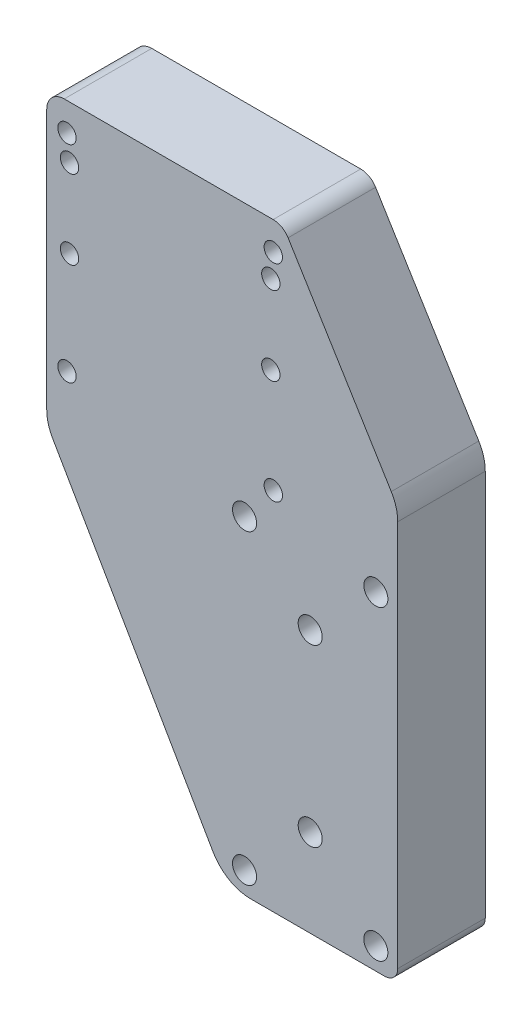
SolidWorks part; units mm, degrees
ref_plane "Front Plane" through (0, 0, 0) normal (0, 0, 1) x (1, 0, 0)
ref_plane "Top Plane" through (0, 0, 0) normal (0, 1, 0) x (1, 0, 0)
ref_plane "Right Plane" through (0, 0, 0) normal (1, 0, 0) x (0, 0, -1)
sketch "Sketch1" plane through (0, 0, 0) normal (0, 0, 1) x (1, 0, 0)
  line L0 (-130, 510) -> (13.8884, 510) construction
  line L1 (-170.2, 540.8246) -> (-129.3094, 470)
  line L2 (-116.2253, 607) -> (-90, 564.2553)
  line L15 (-90, 473) -> (-90, 564.2553)
  line L16 (-90, 473) -> (-90, 547) construction
  line L24 (-170.2, 540.8246) -> (-170.2, 607)
  line L25 (-170.2, 607) -> (-116.2253, 607)
  line L183 (-129.3094, 470) -> (-93, 470)
  arc A1 (-113.8, 602.2) -> (-116.8, 605.2) centre (-116.8, 602.2) ccw construction
  arc A13 (-90, 473) -> (-93, 470) centre (-93, 473) cw
extrude "Boss-Extrude1" add sketch "Sketch1" along normal blind 20
fillet "Fillet1" radius 10 3 edges at (-129.3094, 470, 10) (-170.2, 540.8246, 10) (-90, 564.2553, 10)
sketch "Sketch2" plane through (0, 0, 20) normal (0, 0, 1) x (1, 0, 0)
  circle A0 centre (-142, 577) radius 20
  dimension "D1" = 40
hole_wizard "Tap Drill for M5 Tap1" positions "Sketch5" profile "Sketch6" hole size "M5" standard "ISO" end condition through all
sketch "Sketch5" plane through (0, 0, 0) normal (0, 0, -1) x (-1, 0, 0)
  line L1 (119, 595) -> (119, 577)
  line L2 (119, 595) -> (165, 595)
  line L3 (165, 595) -> (165, 577)
  line L4 (119, 577) -> (165, 577)
  circle A1 centre (119, 595) radius 2.1
  point P2 (119, 595)
  point P4 (119, 577)
  point P6 (165, 577)
  point P8 (165, 595)
  dimension "D1" = 18
  dimension "D2" = 46
  dimension "D3" = 46
  dimension "D4" = 18
sketch "Sketch6" plane through (-119, 595, 0) normal (1, 0, 0) x (0, 1, 0)
  line L0 (0, 0) -> (0, 20)
  line L1 (0, 20) -> (2.1, 20)
  line L2 (2.1, 20) -> (2.1, 0)
  line L5 (2.1, 0) -> (0, 0)
  line L11 (0, -6.35) -> (0, 107.95) construction
  dimension "Thru Hole Dia." = 4.2
  dimension "Thru Hole Depth" = 20
hole_wizard "M5 Clearance Hole1" positions "Sketch7" profile "Sketch8" hole size "M5" standard "ISO" end condition through all
sketch "Sketch7" plane through (0, 0, 20) normal (0, 0, 1) x (1, 0, 0)
  point P0 (-95, 545)
  point P2 (-125, 545)
  point P4 (-125, 475)
  point P6 (-95, 475)
  point P8 (-110, 490)
  point P10 (-110, 530)
sketch "Sketch8" plane through (-95, 545, 20) normal (1, 0, 0) x (0, -1, 0)
  line L0 (0, 0) -> (0, 20)
  line L1 (0, 20) -> (2.75, 20)
  line L2 (2.75, 20) -> (2.75, 0)
  line L5 (2.75, 0) -> (0, 0)
  line L11 (0, -6.35) -> (0, 107.95) construction
  dimension "Thru Hole Dia." = 5.5
  dimension "Thru Hole Depth" = 20
hole_wizard "Tap Drill for M5 Tap2" positions "Sketch9" profile "Sketch10" hole size "M5" standard "ISO" end condition through all
sketch "Sketch9" plane through (0, 0, 20) normal (0, 0, 1) x (1, 0, 0)
  point P0 (-165.57, 553.43)
  point P2 (-165.57, 600.57)
  point P4 (-118.43, 553.43)
  point P6 (-118.43, 600.57)
sketch "Sketch10" plane through (-165.57, 553.43, 20) normal (1, 0, 0) x (0, -1, 0)
  line L0 (0, 0) -> (0, 20)
  line L1 (0, 20) -> (2.1, 20)
  line L2 (2.1, 20) -> (2.1, 0)
  line L5 (2.1, 0) -> (0, 0)
  line L11 (0, -6.35) -> (0, 107.95) construction
  dimension "Thru Hole Dia." = 4.2
  dimension "Thru Hole Depth" = 20
fillet "Fillet2" radius 4 2 edges at (-116.2253, 607, 10) (-170.2, 607, 10)
